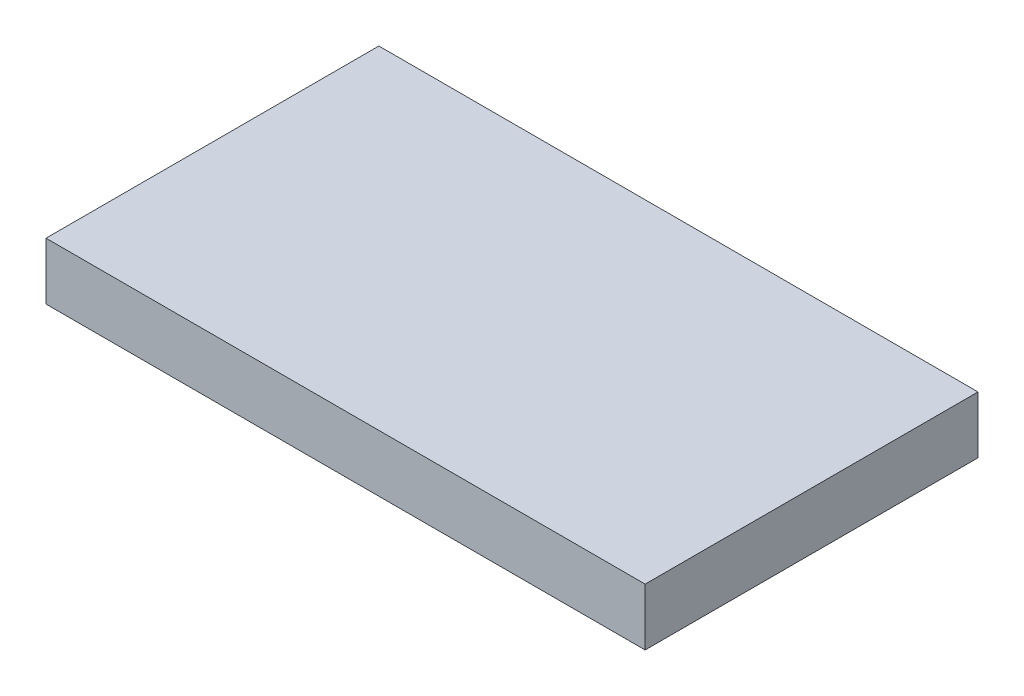
SolidWorks part; units mm, degrees
ref_plane "Спереди" through (0, 0, 0) normal (0, 0, 1) x (1, 0, 0)
ref_plane "Сверху" through (0, 0, 0) normal (0, 1, 0) x (1, 0, 0)
ref_plane "Справа" through (0, 0, 0) normal (1, 0, 0) x (0, 0, -1)
sketch "Эскиз1" plane through (0, 0, 0) normal (0, 1, 0) x (1, 0, 0)
  line L1 (0, 0) -> (63, 0)
  line L2 (0, 0) -> (0, 35)
  line L3 (0, 35) -> (63, 35)
  line L4 (63, 0) -> (63, 35)
  dimension "D1" = 35
  dimension "D2" = 63
extrude "Бобышка-Вытянуть1" add sketch "Эскиз1" along normal blind 6 contours L3 L4 L1 L2
